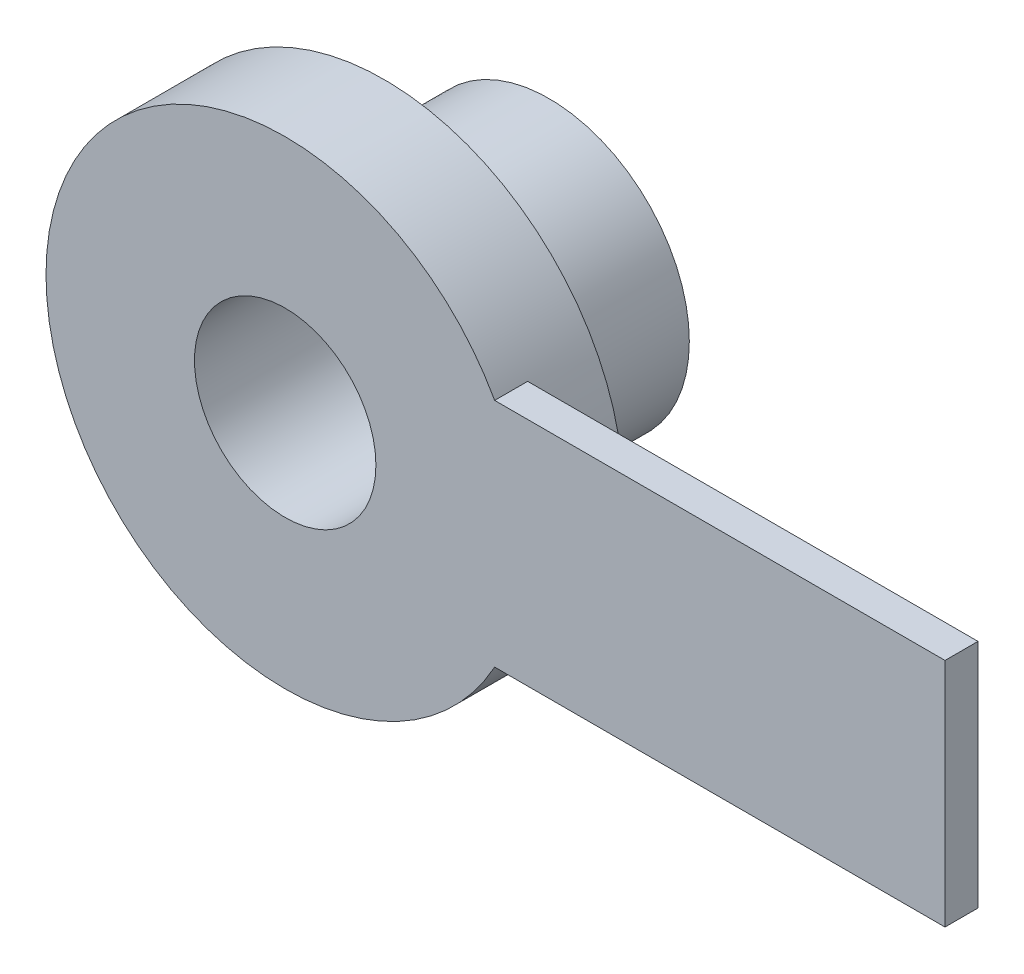
SolidWorks part; units mm, degrees
ref_plane "Спереди" through (0, 0, 0) normal (0, 0, 1) x (1, 0, 0)
ref_plane "Сверху" through (0, 0, 0) normal (0, 1, 0) x (1, 0, 0)
ref_plane "Справа" through (0, 0, 0) normal (1, 0, 0) x (0, 0, -1)
ref_plane "Плоскость4" through (0, 0, 0) normal (0, -1, 0) x (1, 0, 0)
sketch "Эскиз1" plane through (0, 0, 0) normal (0, -1, 0) x (1, 0, 0)
  line L0 (7.25, 3) -> (0, 3)
  line L1 (0, 3) -> (0, 0)
  line L2 (0, 0) -> (7.25, 0)
  line L3 (7.25, 0) -> (7.25, 3)
  line L4 (0, 3) -> (0, 0) construction
revolve "Повернуть1" add sketch "Эскиз1" angle 360 about L4
ref_plane "Плоскость5" through (20, 0, 0) normal (1, 0, 0) x (0, 0, -1)
sketch "Эскиз2" plane through (20, 0, 0) normal (1, 0, 0) x (0, 0, -1)
  line L0 (-2, 3.5) -> (-3, 3.5)
  line L1 (-3, 3.5) -> (-3, -3.5)
  line L2 (-3, -3.5) -> (-2, -3.5)
  line L3 (-2, -3.5) -> (-2, 3.5)
extrude "Бобышка-Вытянуть1" add sketch "Эскиз2" against normal up to next
sketch "Эскиз3" plane through (0, 0, 0) normal (0, 0, -1) x (-1, 0, 0)
  circle A0 centre (0, 0) radius 4.25
extrude "Бобышка-Вытянуть2" add sketch "Эскиз3" along normal blind 5
hole_wizard "Диаметр отверстия Ø5.5 (5.5)1" positions "Эскиз5" profile "Эскиз4" hole size "Ø5.5" standard "Ansi Metric"
sketch "Эскиз5" plane through (0, 0, 3) normal (0, 0, 1) x (1, 0, 0)
  point P0 (0, 0)
sketch "Эскиз4" plane through (0, 0, 3) normal (1, 0, 0) x (0, -1, 0)
  line L0 (0, 0) -> (0, 8)
  line L1 (0, 8) -> (2.75, 8)
  line L2 (2.75, 8) -> (2.75, 0)
  line L5 (2.75, 0) -> (0, 0)
  line L11 (0, -6.35) -> (0, 107.95) construction
  dimension "Диаметр сквозного отверстия" = 5.5
  dimension "Глубина сквозного отверстия" = 8
